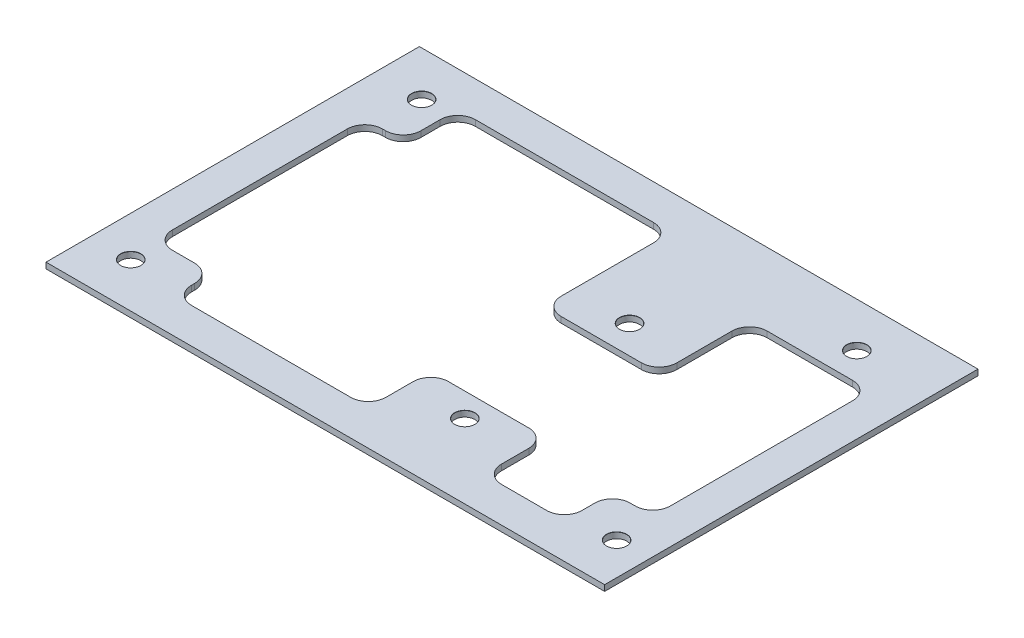
SolidWorks part; units mm, degrees
ref_plane "Front Plane" through (0, 0, 0) normal (0, 0, 1) x (1, 0, 0)
ref_plane "Top Plane" through (0, 0, 0) normal (0, 1, 0) x (1, 0, 0)
ref_plane "Right Plane" through (0, 0, 0) normal (1, 0, 0) x (0, 0, -1)
sketch "Sketch2" plane through (0, 0, 0) normal (0, 1, 0) x (1, 0, 0)
  line L1 (47.5, 31.75) -> (-47.5, 31.75)
  line L2 (47.5, 31.75) -> (47.5, -31.75)
  line L3 (47.5, -31.75) -> (-47.5, -31.75)
  line L4 (-47.5, 31.75) -> (-47.5, -31.75)
  line L5 (47.5, 31.75) -> (-47.5, -31.75) construction
  line L6 (47.5, -31.75) -> (-47.5, 31.75) construction
  point P0 (0, 0)
  dimension "D1" = 95
  dimension "D2" = 63.5
extrude "Boss-Extrude1" add sketch "Sketch2" along normal blind 1
hole_wizard "M3 Clearance Hole1" positions "Sketch7" profile "Sketch8" hole size "M3" standard "ANSI Metric" end condition through all
sketch "Sketch7" plane through (0, 1, 0) normal (0, 1, 0) x (1, 0, 0)
  line L1 (-40.6667, 24.17) -> (34.4633, 24.17)
  line L2 (-40.6667, 24.17) -> (-40.6667, -24.17)
  line L3 (-40.6667, -24.17) -> (34.4633, -24.17)
  line L4 (34.4633, 24.17) -> (34.4633, -24.17)
  line L5 (34.4633, -24.17) -> (41.9633, -24.17) construction
  line L12 (41.9633, -24.17) -> (47.5, -24.17) construction
  line L13 (47.5, -31.75) -> (47.5, 31.75) construction
  line L15 (0, 31.75) -> (0, 24.17) construction
  line L16 (47.5, 31.75) -> (-47.5, 31.75) construction
  line L17 (-3.1017, -24.17) -> (-3.1017, -31.75) construction
  line L18 (-47.5, -31.75) -> (47.5, -31.75) construction
  line L19 (11.1433, -19.17) -> (11.1433, -24.17) construction
  point P33 (-40.6667, -24.17)
  point P34 (34.4633, 24.17)
  point P43 (41.9633, -24.17)
  point P74 (11.1433, -19.17)
  point P80 (11.1433, 8.85)
  point P85 (-3.1017, -24.17)
  point P89 (-39.5367, 24.17)
  dimension "D1" = 48.34
  dimension "D2" = 75.13
  dimension "D3" = 7.5
  dimension "D4" = 51.81
  dimension "D5" = 5
  dimension "D6" = 28.02
  dimension "D7" = 1.13
sketch "Sketch8" plane through (-39.5367, 1, -24.17) normal (1, 0, 0) x (0, 0, 1)
  line L0 (0, 0) -> (0, 1)
  line L1 (0, 1) -> (1.7, 1)
  line L2 (1.7, 1) -> (1.7, 0.025)
  line L3 (1.7, 0.025) -> (1.725, 0)
  line L5 (1.725, 0) -> (0, 0)
  line L6 (-1.7, 0.025) -> (-1.725, 0) construction
  line L11 (0, -6.35) -> (0, 107.95) construction
  dimension "Thru Hole Dia." = 3.4
  dimension "Thru Hole Depth" = 1
  dimension "Near C'Sink Dia." = 3.45
  dimension "Near C'Sink Angle" = 90
sketch "Sketch9" plane through (0, 1, 0) normal (0, 1, 0) x (1, 0, 0)
  line L0 (-34.9742, 19.4874) -> (-34.9742, 22.75)
  line L2 (-37.9742, 16.4874) -> (-38.5, 16.4874)
  line L3 (-41.5, 13.4874) -> (-41.5, -16.2525)
  line L4 (-38.5, -19.2525) -> (-34.7301, -19.2525)
  line L5 (-31.7301, -22.2525) -> (-31.7301, -22.75)
  line L6 (-31.9742, 25.75) -> (-1.6848, 25.75)
  line L7 (-28.7301, -25.75) -> (-1.6848, -25.75)
  line L8 (1.3152, -22.75) -> (1.3152, -18.118)
  line L9 (4.3152, -15.118) -> (17.9713, -15.118)
  line L10 (20.9713, -18.118) -> (20.9713, -22.75)
  line L11 (23.9713, -25.75) -> (31.6479, -25.75)
  line L12 (34.6479, -22.75) -> (34.6479, -20.5605)
  line L13 (37.6479, -17.5605) -> (38.5, -17.5605)
  line L14 (41.5, -14.5605) -> (41.5, 16.4283)
  line L15 (38.5, 19.4283) -> (23.9713, 19.4283)
  line L16 (20.9713, 16.4283) -> (20.9713, 7.055)
  line L17 (17.9713, 4.055) -> (4.3152, 4.055)
  line L18 (1.3152, 7.055) -> (1.3152, 22.75)
  line L19 (-47.5, 31.75) -> (-47.5, -31.75) construction
  line L20 (47.5, 31.75) -> (-47.5, 31.75) construction
  line L21 (47.5, -31.75) -> (47.5, 31.75) construction
  line L22 (-47.5, -31.75) -> (47.5, -31.75) construction
  circle A0 centre (41.9633, -24.17) radius 1.725 construction
  circle A1 centre (34.4633, 24.17) radius 1.725 construction
  circle A2 centre (11.1433, 8.85) radius 1.725 construction
  circle A3 centre (11.1433, -19.17) radius 1.725 construction
  circle A4 centre (-40.6667, -24.17) radius 1.725 construction
  circle A5 centre (-40.6667, 24.17) radius 1.725 construction
  circle A6 centre (41.9633, -24.17) radius 1.725 construction
  circle A7 centre (34.4633, 24.17) radius 1.725 construction
  circle A8 centre (11.1433, 8.85) radius 1.725 construction
  circle A9 centre (11.1433, -19.17) radius 1.725 construction
  circle A10 centre (-40.6667, -24.17) radius 1.725 construction
  circle A11 centre (-40.6667, 24.17) radius 1.725 construction
  arc A12 (-34.9742, 22.75) -> (-31.9742, 25.75) centre (-31.9742, 22.75) cw
  arc A13 (-1.6848, 25.75) -> (1.3152, 22.75) centre (-1.6848, 22.75) cw
  arc A14 (4.3152, 4.055) -> (1.3152, 7.055) centre (4.3152, 7.055) cw
  arc A15 (20.9713, 7.055) -> (17.9713, 4.055) centre (17.9713, 7.055) cw
  arc A16 (23.9713, 19.4283) -> (20.9713, 16.4283) centre (23.9713, 16.4283) ccw
  arc A17 (41.5, 16.4283) -> (38.5, 19.4283) centre (38.5, 16.4283) ccw
  arc A18 (38.5, -17.5605) -> (41.5, -14.5605) centre (38.5, -14.5605) ccw
  arc A19 (34.6479, -20.5605) -> (37.6479, -17.5605) centre (37.6479, -20.5605) cw
  arc A20 (31.6479, -25.75) -> (34.6479, -22.75) centre (31.6479, -22.75) ccw
  arc A21 (20.9713, -22.75) -> (23.9713, -25.75) centre (23.9713, -22.75) ccw
  arc A22 (17.9713, -15.118) -> (20.9713, -18.118) centre (17.9713, -18.118) cw
  arc A23 (1.3152, -18.118) -> (4.3152, -15.118) centre (4.3152, -18.118) cw
  arc A24 (-1.6848, -25.75) -> (1.3152, -22.75) centre (-1.6848, -22.75) ccw
  arc A25 (-31.7301, -22.75) -> (-28.7301, -25.75) centre (-28.7301, -22.75) ccw
  arc A26 (-34.7301, -19.2525) -> (-31.7301, -22.2525) centre (-34.7301, -22.2525) cw
  arc A27 (-41.5, -16.2525) -> (-38.5, -19.2525) centre (-38.5, -16.2525) ccw
  arc A28 (-38.5, 16.4874) -> (-41.5, 13.4874) centre (-38.5, 13.4874) ccw
  arc A29 (-34.9742, 19.4874) -> (-37.9742, 16.4874) centre (-37.9742, 19.4874) cw
  point P37 (11.1433, -15.118)
  point P39 (11.1433, 4.055)
  dimension "D5" = 3
  dimension "D1" = 6
  dimension "D2" = 6
  dimension "D3" = 6
  dimension "D4" = 6
extrude "Cut-Extrude1" cut sketch "Sketch9" against normal up to surface (1 mm away) up to face at (-40.6667, 0, 25.87)
sketch "Sketch10" plane through (0, 0, 0) normal (0, -1, 0) x (1, 0, 0)
  line L1 (-41.4017, 20.903) -> (-38.2049, 21.9)
  line L2 (-38.2049, 21.9) -> (-37.47, 25.167)
  line L3 (-37.47, 25.167) -> (-39.9318, 27.437)
  line L4 (-39.9318, 27.437) -> (-43.1285, 26.44)
  line L5 (-43.1285, 26.44) -> (-43.8635, 23.173)
  line L6 (-43.8635, 23.173) -> (-41.4017, 20.903)
  line L7 (-41.9734, -27.2532) -> (-38.65, -26.8432)
  line L8 (-38.65, -26.8432) -> (-37.3433, -23.76)
  line L9 (-37.3433, -23.76) -> (-39.3601, -21.0868)
  line L10 (-39.3601, -21.0868) -> (-42.6835, -21.4968)
  line L11 (-42.6835, -21.4968) -> (-43.9902, -24.58)
  line L12 (-43.9902, -24.58) -> (-41.9734, -27.2532)
  line L13 (8.0727, -10.1861) -> (10.7651, -12.1772)
  line L14 (10.7651, -12.1772) -> (13.8356, -10.8411)
  line L15 (13.8356, -10.8411) -> (14.2138, -7.5139)
  line L16 (14.2138, -7.5139) -> (11.5215, -5.5228)
  line L17 (11.5215, -5.5228) -> (8.4509, -6.8589)
  line L18 (8.4509, -6.8589) -> (8.0727, -10.1861)
  line L19 (8.0802, 17.8169) -> (10.7835, 15.8407)
  line L20 (10.7835, 15.8407) -> (13.8466, 17.1938)
  line L21 (13.8466, 17.1938) -> (14.2064, 20.5231)
  line L22 (14.2064, 20.5231) -> (11.503, 22.4993)
  line L23 (11.503, 22.4993) -> (8.4399, 21.1462)
  line L24 (8.4399, 21.1462) -> (8.0802, 17.8169)
  line L25 (32.6053, -26.9559) -> (35.9469, -27.172)
  line L26 (35.9469, -27.172) -> (37.8049, -24.3861)
  line L27 (37.8049, -24.3861) -> (36.3212, -21.3841)
  line L28 (36.3212, -21.3841) -> (32.9796, -21.168)
  line L29 (32.9796, -21.168) -> (31.1216, -23.9539)
  line L30 (31.1216, -23.9539) -> (32.6053, -26.9559)
  line L31 (40.0405, 21.4284) -> (43.3761, 21.134)
  line L32 (43.3761, 21.134) -> (45.2989, 23.8756)
  line L33 (45.2989, 23.8756) -> (43.8861, 26.9116)
  line L34 (43.8861, 26.9116) -> (40.5504, 27.206)
  line L35 (40.5504, 27.206) -> (38.6276, 24.4644)
  line L36 (38.6276, 24.4644) -> (40.0405, 21.4284)
  circle A0 centre (34.4633, -24.17) radius 1.7 construction
  circle A1 centre (41.9633, 24.17) radius 1.7 construction
  circle A2 centre (11.1433, 19.17) radius 1.7 construction
  circle A3 centre (11.1433, -8.85) radius 1.7 construction
  circle A4 centre (-40.6667, -24.17) radius 1.7 construction
  circle A5 centre (-40.6667, 24.17) radius 1.7 construction
  circle A6 centre (34.4633, -24.17) radius 1.7 construction
  circle A7 centre (41.9633, 24.17) radius 1.7 construction
  circle A8 centre (11.1433, 19.17) radius 1.7 construction
  circle A9 centre (11.1433, -8.85) radius 1.7 construction
  circle A10 centre (-40.6667, -24.17) radius 1.7 construction
  circle A11 centre (-40.6667, 24.17) radius 1.7 construction
  circle A12 centre (-40.6667, 24.17) radius 2.9 construction
  circle A13 centre (-40.6667, -24.17) radius 2.9 construction
  circle A14 centre (11.1433, -8.85) radius 2.9 construction
  circle A15 centre (11.1433, 19.17) radius 2.9 construction
  circle A16 centre (34.4633, -24.17) radius 2.9 construction
  circle A17 centre (41.9633, 24.17) radius 2.9 construction
  dimension "D1" = 5.8
extrude "Cut-Extrude2" [suppressed] cut sketch "Sketch10" against normal blind 2.4
fillet "Fillet2" [suppressed] radius 2
sketch "Sketch12" [suppressed] plane through (0, 11, 0) normal (0, 1, 0) x (1, 0, 0)
  line L0 (-31.7301, -22.2525) -> (-31.7301, -22.75) construction
  line L1 (-38.5, -19.2525) -> (-34.7301, -19.2525) construction
  line L2 (-31.7301, -22.2525) -> (-31.7301, -22.75)
  line L3 (-38.5, -19.2525) -> (-34.7301, -19.2525)
  line L4 (-47.5, 31.75) -> (-47.5, -31.75)
  line L5 (-47.5, -31.75) -> (47.5, -31.75)
  line L6 (47.5, -31.75) -> (47.5, 31.75)
  line L7 (47.5, 31.75) -> (-47.5, 31.75)
  line L8 (-47.5, 31.75) -> (-47.5, -31.75)
  line L9 (-47.5, -31.75) -> (47.5, -31.75)
  line L10 (47.5, -31.75) -> (47.5, 31.75)
  line L11 (47.5, 31.75) -> (-47.5, 31.75)
  line L12 (-41.5, -16.2525) -> (-47.5, -16.2525) construction
  line L13 (-28.7301, -25.75) -> (-28.7301, -31.75) construction
  line L14 (-40.6667, -24.17) -> (-40.6213, -18.3738) construction
  arc A0 (-31.7301, -22.75) -> (-28.7301, -25.75) centre (-28.7301, -22.75) ccw construction
  arc A1 (-31.7301, -22.2525) -> (-34.7301, -19.2525) centre (-34.7301, -22.2525) ccw construction
  arc A2 (-41.5, -16.2525) -> (-38.5, -19.2525) centre (-38.5, -16.2525) ccw construction
  arc A3 (-31.7301, -22.75) -> (-28.7301, -25.75) centre (-28.7301, -22.75) ccw
  arc A4 (-31.7301, -22.2525) -> (-34.7301, -19.2525) centre (-34.7301, -22.2525) ccw
  arc A5 (-41.5, -16.2525) -> (-38.5, -19.2525) centre (-38.5, -16.2525) ccw
  circle A6 centre (-40.6667, -24.17) radius 1.7 construction
  circle A7 centre (-40.6667, -24.17) radius 1.7
  dimension "D1" = 0
sketch "Sketch13" plane through (0, 1, 0) normal (0, 1, 0) x (1, 0, 0)
  circle A0 centre (-39.5367, 24.17) radius 1.725 construction
  circle A1 centre (-40.6667, -24.17) radius 1.725 construction
  circle A2 centre (-39.5367, 24.17) radius 1.725
  circle A3 centre (-40.6667, -24.17) radius 1.725
  point P6 (0, 0)
  point P7 (0, 0)
  point P8 (0, 0)
  point P9 (0, 0)
  point P10 (0, 0)
